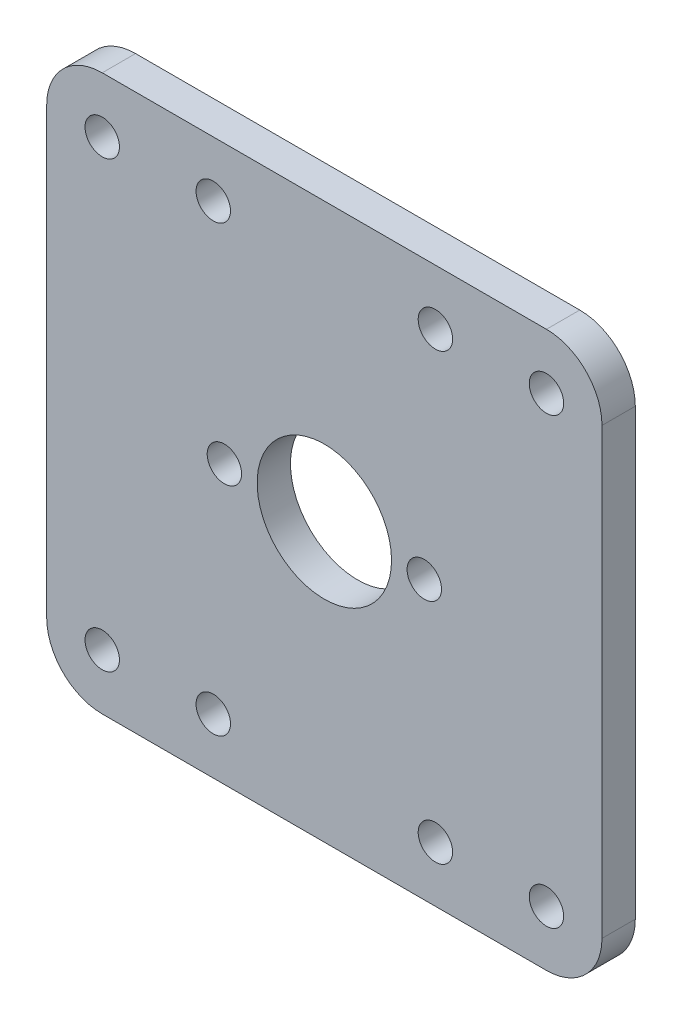
SolidWorks part; units mm, degrees
ref_plane "正面" through (0, 0, 0) normal (0, 0, 1) x (1, 0, 0)
ref_plane "平面" through (0, 0, 0) normal (0, 1, 0) x (1, 0, 0)
ref_plane "右側面" through (0, 0, 0) normal (1, 0, 0) x (0, 0, -1)
sketch "ｽｹｯﾁ1" plane through (0, 0, 0) normal (0, 0, 1) x (1, 0, 0)
  line L0 (0, 25) -> (0, -25) construction
  line L1 (-25, 25) -> (25, 25)
  line L2 (-25, 25) -> (-25, -25)
  line L3 (-25, -25) -> (25, -25)
  line L4 (25, 25) -> (25, -25)
  line L5 (-25, 25) -> (25, -25) construction
  line L6 (-25, -25) -> (25, 25) construction
  line L7 (0, 0) -> (-9, 0) construction
  circle A0 centre (-20, 20) radius 1.55
  circle A1 centre (20, 20) radius 1.55
  circle A2 centre (20, -20) radius 1.55
  circle A3 centre (-20, -20) radius 1.55
  circle A4 centre (0, 0) radius 6.05
  circle A5 centre (-9, 0) radius 1.55
  circle A6 centre (9, 0) radius 1.55
  point P0 (0, 0)
  dimension "D2" = 4
  dimension "D4" = 3.1
  dimension "D5" = 12.1
  dimension "D6" = 3.1
  dimension "D1" = 50
  dimension "D3" = 40
  dimension "D7" = 9
extrude "ﾎﾞｽ - 押し出し1" add sketch "ｽｹｯﾁ1" along normal blind 3
fillet "ﾌｨﾚｯﾄ1" radius 5 4 edges at (-25, -25, 1.5) (25, -25, 1.5) (25, 25, 1.5) (-25, 25, 1.5)
sketch "ｽｹｯﾁ2" plane through (0, 0, 3) normal (0, 0, 1) x (1, 0, 0)
  line L0 (0, 0) -> (0, 25) construction
  line L1 (20, 25) -> (-20, 25) construction
  line L2 (0, 20) -> (-10, 20) construction
  line L3 (-25, 0) -> (25, 0) construction
  line L4 (-25, 20) -> (-25, -20) construction
  line L5 (25, -20) -> (25, 20) construction
  circle A0 centre (-10, 20) radius 1.55
  circle A1 centre (10, 20) radius 1.55
  circle A2 centre (10, -20) radius 1.55
  circle A3 centre (-10, -20) radius 1.55
  dimension "D1" = 10
  dimension "D2" = 3.1
extrude "ｶｯﾄ - 押し出し1" cut sketch "ｽｹｯﾁ2" against normal through all
